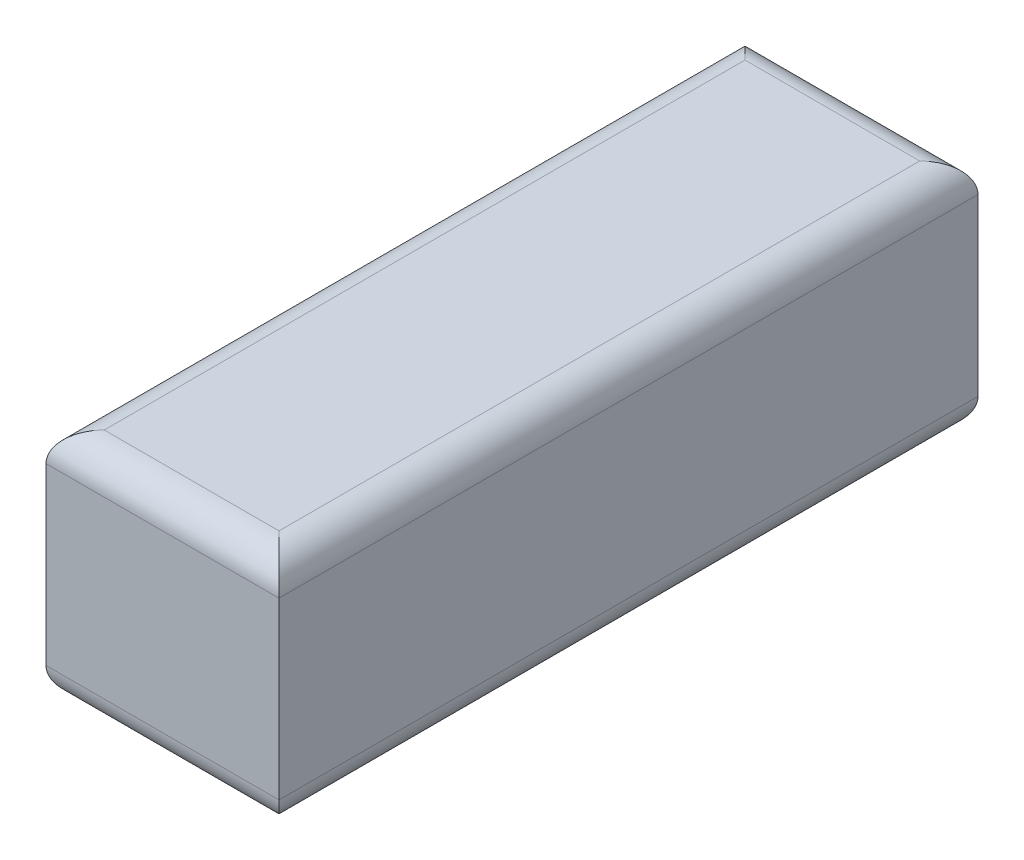
SolidWorks part; units mm, degrees
ref_plane "Front Plane" through (0, 0, 0) normal (0, 0, 1) x (1, 0, 0)
ref_plane "Top Plane" through (0, 0, 0) normal (0, 1, 0) x (1, 0, 0)
ref_plane "Right Plane" through (0, 0, 0) normal (1, 0, 0) x (0, 0, -1)
sketch "Sketch1" plane through (0, 0, 0) normal (0, 0, 1) x (1, 0, 0)
  line L1 (304.8, -304.8) -> (-304.8, -304.8)
  line L2 (304.8, -304.8) -> (304.8, 304.8)
  line L3 (304.8, 304.8) -> (-304.8, 304.8)
  line L4 (-304.8, -304.8) -> (-304.8, 304.8)
  line L5 (304.8, -304.8) -> (-304.8, 304.8) construction
  line L6 (304.8, 304.8) -> (-304.8, -304.8) construction
  point P0 (0, 0)
  dimension "D1" = 609.6
  dimension "D2" = 609.6
extrude "Boss-Extrude1" add sketch "Sketch1" along normal blind 1828.8
fillet "Fillet1" radius 76.2 8 edges at (0, 304.8, 0) (0, -304.8, 0) (0, 304.8, 1828.8) (0, -304.8, 1828.8) (-304.8, -304.8, 914.4) (-304.8, 304.8, 914.4) (304.8, 304.8, 914.4) (304.8, -304.8, 914.4)
